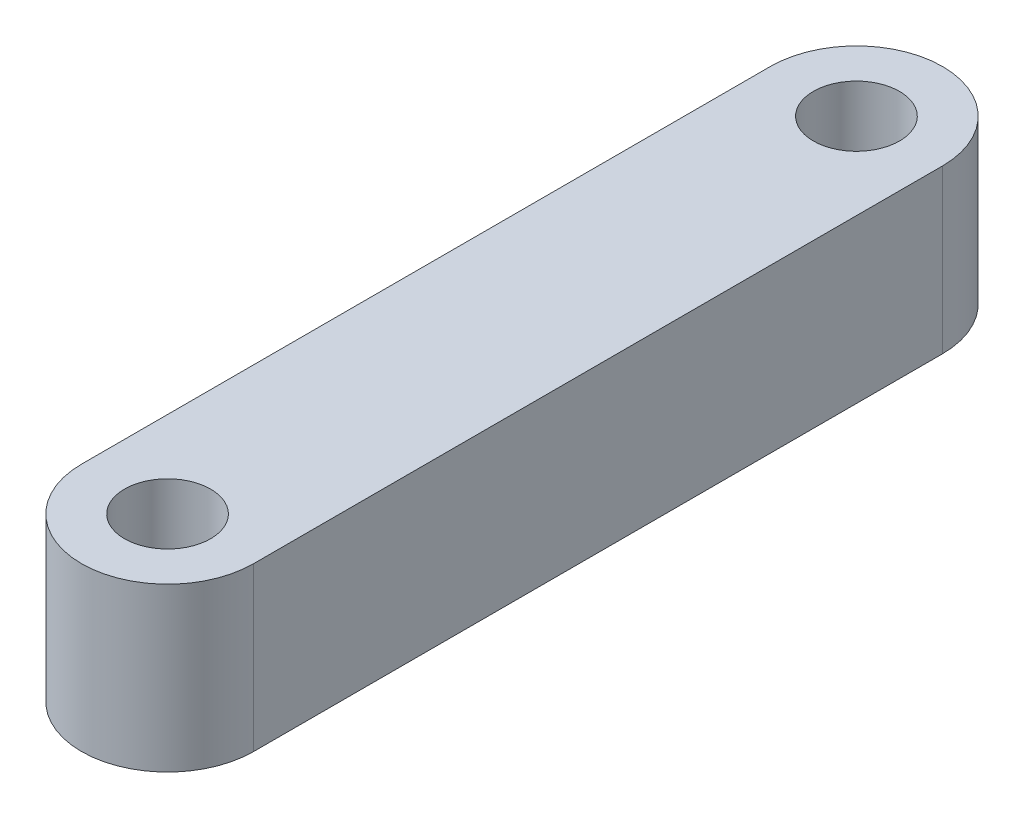
SolidWorks part; units mm, degrees
material "PLA"
ref_plane "Front Plane" through (0, 0, 0) normal (0, 0, 1) x (1, 0, 0)
ref_plane "Top Plane" through (0, 0, 0) normal (0, 1, 0) x (1, 0, 0)
ref_plane "Right Plane" through (0, 0, 0) normal (1, 0, 0) x (0, 0, -1)
sketch "Sketch1" plane through (0, 0, 0) normal (0, 1, 0) x (1, 0, 0)
  line L0 (-3.175, 25.4) -> (-3.175, 0)
  line L1 (3.175, 25.4) -> (3.175, 0)
  circle A0 centre (0, 0) radius 1.5875
  arc A1 (-3.175, 0) -> (3.175, 0) centre (0, 0) ccw
  circle A4 centre (0, 25.4) radius 1.5875
  arc A5 (3.175, 25.4) -> (-3.175, 25.4) centre (0, 25.4) ccw
  dimension "D2" = 6.35
  dimension "D3" = 3.175
  dimension "D1" = 25.4
  dimension "D4" = 6.35
extrude "Boss-Extrude1" add sketch "Sketch1" along normal blind 6
